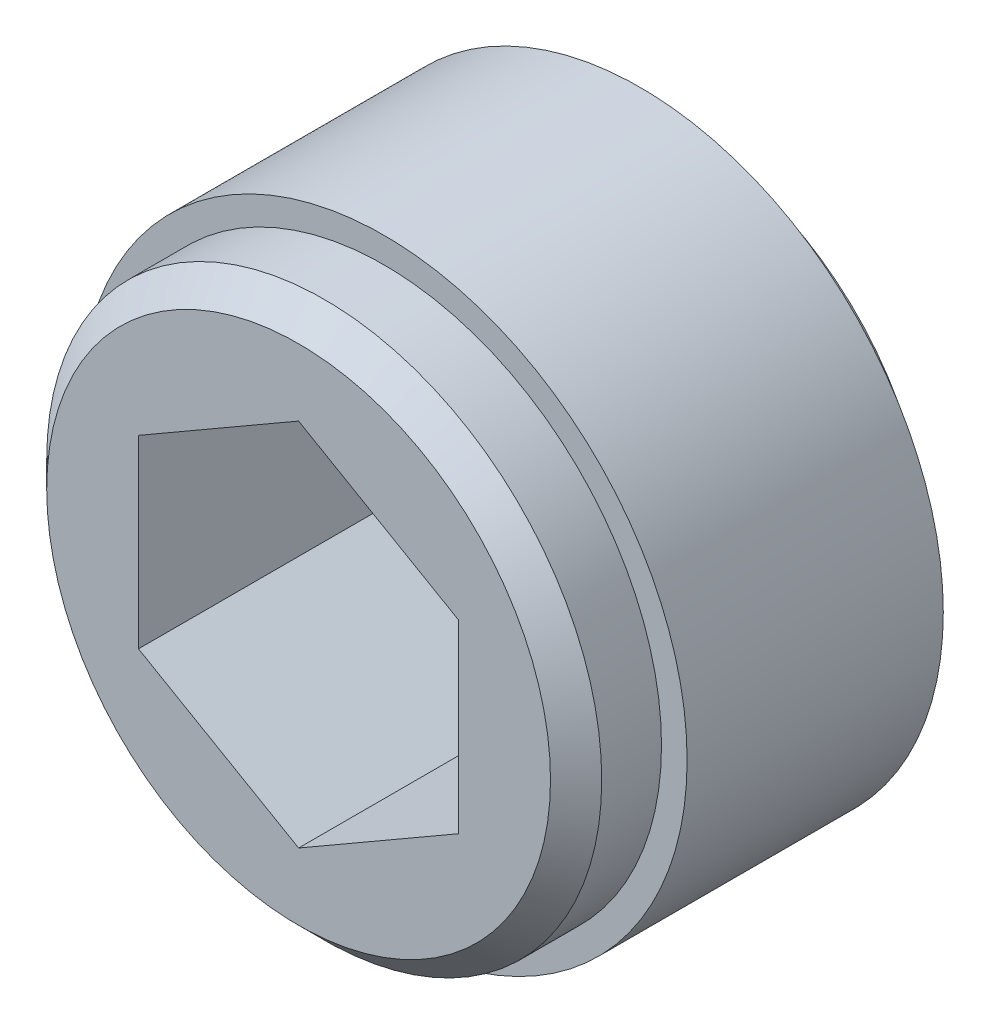
SolidWorks part; units mm, degrees
material "Plain Carbon Steel"
ref_plane "Front Plane" through (0, 0, 0) normal (0, 0, 1) x (1, 0, 0)
ref_plane "Top Plane" through (0, 0, 0) normal (0, 1, 0) x (1, 0, 0)
ref_plane "Right Plane" through (0, 0, 0) normal (1, 0, 0) x (0, 0, -1)
sketch "Sketch1" plane through (0, 0, 0) normal (0, 0, 1) x (1, 0, 0)
  circle A0 centre (0, 0) radius 4.5085
  dimension "D1" = 9.017
extrude "Boss-Extrude1" add sketch "Sketch1" along normal blind 5.08
cosmetic thread "Cosmetic Thread1" parameters "D2"=6.2586
sketch "Sketch2" plane through (0, 0, 0) normal (0, 0, -1) x (-1, 0, 0)
  circle A0 centre (0, 0) radius 3.81
  dimension "D1" = 7.62
extrude "Boss-Extrude2" add sketch "Sketch2" along normal blind 0.635 draft 15
sketch "Sketch3" plane through (0, 0, 5.08) normal (0, 0, 1) x (1, 0, 0)
  circle A0 centre (0, 0) radius 4.1275
  circle A1 centre (0, 0) radius 4.5085 construction
  circle A2 centre (0, 0) radius 4.5085
  circle M3 centre (0, 0) radius 4.5085
  dimension "D1" = 8.255
extrude "Cut-Extrude1" cut sketch "Sketch3" against normal blind 1.27 contours A0 M3
chamfer "Chamfer1" distance 0.381 1 edges at (4.1275, 0, 5.08)
sketch "Sketch4" plane through (0, 0, 5.08) normal (0, 0, 1) x (1, 0, 0)
  line L1 (0, -2.7496) -> (2.3813, -1.3748)
  line L2 (2.3813, -1.3748) -> (2.3813, 1.3748)
  line L3 (2.3813, 1.3748) -> (0, 2.7496)
  line L4 (0, 2.7496) -> (-2.3813, 1.3748)
  line L5 (-2.3813, 1.3748) -> (-2.3813, -1.3748)
  line L6 (-2.3813, -1.3748) -> (0, -2.7496)
  circle A0 centre (0, 0) radius 2.3813 construction
  dimension "D1" = 4.7625
extrude "Cut-Extrude2" cut sketch "Sketch4" against normal through all
